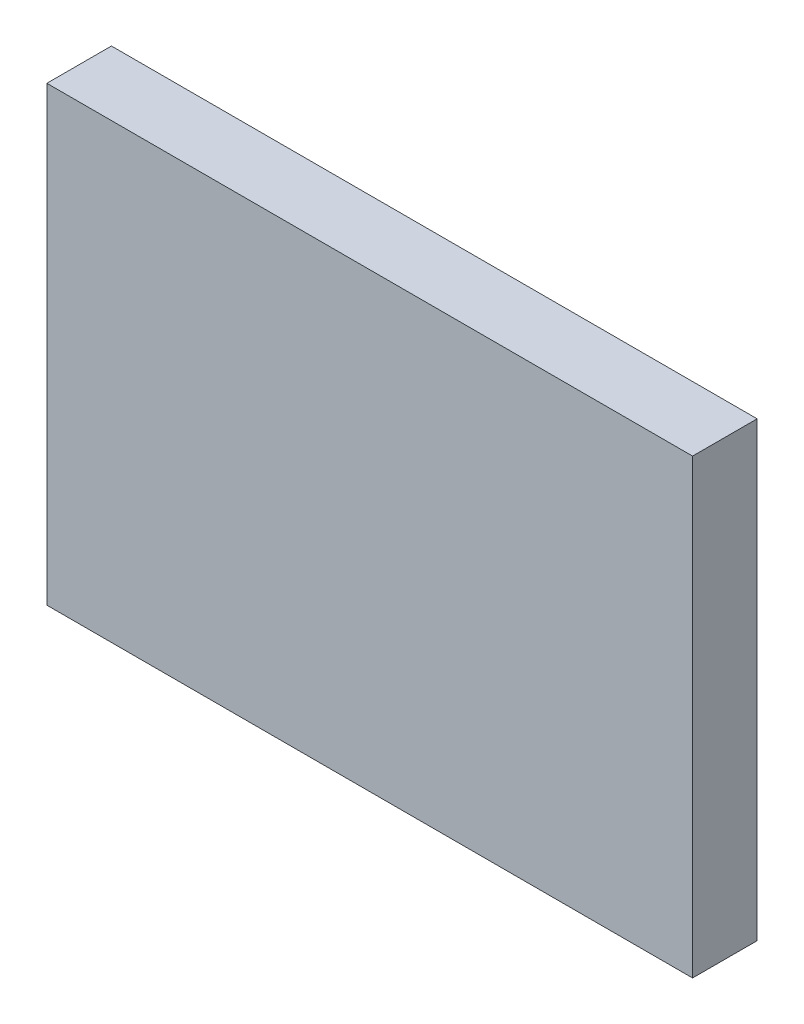
SolidWorks part; units mm, degrees
ref_plane "前视基准面" through (0, 0, 0) normal (0, 0, 1) x (1, 0, 0)
ref_plane "上视基准面" through (0, 0, 0) normal (0, 1, 0) x (1, 0, 0)
ref_plane "右视基准面" through (0, 0, 0) normal (1, 0, 0) x (0, 0, -1)
sketch "草图1" plane through (0, 0, 0) normal (0, 0, 1) x (1, 0, 0)
  line L1 (-5, -3.5) -> (5, -3.5)
  line L2 (-5, -3.5) -> (-5, 3.5)
  line L3 (-5, 3.5) -> (5, 3.5)
  line L4 (5, -3.5) -> (5, 3.5)
  line L5 (-5, -3.5) -> (5, 3.5) construction
  line L6 (-5, 3.5) -> (5, -3.5) construction
  point P0 (0, 0)
  dimension "D1" = 10
  dimension "D2" = 7
extrude "凸台-拉伸1" add sketch "草图1" along normal blind 1
